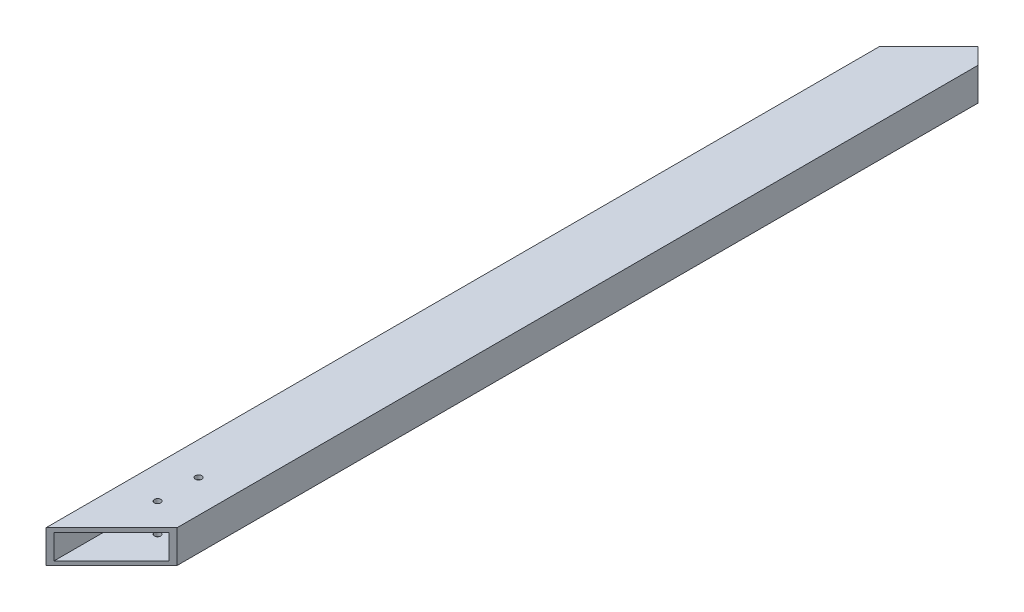
SolidWorks part; units mm, degrees
material "1060 Alloy"
ref_plane "Front Plane" through (0, 0, 0) normal (0, 0, 1) x (1, 0, 0)
ref_plane "Top Plane" through (0, 0, 0) normal (0, 1, 0) x (1, 0, 0)
ref_plane "Right Plane" through (0, 0, 0) normal (1, 0, 0) x (0, 0, -1)
sketch "Sketch1" plane through (0, 0, 0) normal (0, 0, 1) x (1, 0, 0)
  line L0 (22.225, 9.525) -> (-22.225, 9.525)
  line L1 (25.4, -12.7) -> (-25.4, -12.7)
  line L2 (25.4, -12.7) -> (25.4, 12.7)
  line L3 (25.4, 12.7) -> (-25.4, 12.7)
  line L4 (-25.4, -12.7) -> (-25.4, 12.7)
  line L5 (25.4, -12.7) -> (-25.4, 12.7) construction
  line L6 (25.4, 12.7) -> (-25.4, -12.7) construction
  line L7 (-22.225, -9.525) -> (-22.225, 9.525)
  line L8 (22.225, -9.525) -> (-22.225, -9.525)
  line L9 (22.225, -9.525) -> (22.225, 9.525)
  point P0 (0, 0)
  dimension "D1" = 25.4
  dimension "D2" = 50.8
  dimension "D3" = 3.175
extrude "Boss-Extrude1" add sketch "Sketch1" along normal blind 697.2046
sketch "Sketch2" plane through (0, 12.7, 0) normal (0, 1, 0) x (1, 0, 0)
  line L0 (-25.4, -697.2046) -> (25.4, -646.4046)
  line L1 (25.4, -697.2046) -> (25.4, 0) construction
  line L2 (25.4, -646.4046) -> (25.4, -697.2046)
  line L3 (25.4, -697.2046) -> (-25.4, -697.2046)
  line L4 (25.4, 0) -> (-25.4, -50.8)
  line L6 (-25.4, -697.2046) -> (-25.4, 0) construction
  line L7 (-25.4, -50.8) -> (-25.4, 0)
  line L8 (-25.4, 0) -> (25.4, 0)
  dimension "D1" = 45
  dimension "D2" = 45
extrude "Cut-Extrude1" cut sketch "Sketch2" against normal through all
sketch "Sketch3" plane through (0, 12.7, 0) normal (0, 1, 0) x (1, 0, 0)
  line L0 (25.4, 0) -> (25.4, -25.2984)
  line L1 (25.4, -646.4046) -> (25.4, 0) construction
  line L2 (25.4, -25.2984) -> (12.7508, -12.6492)
  line L4 (25.4, 0) -> (12.7508, -12.6492)
  dimension "D1" = 25.2984
  dimension "D2" = 45
extrude "Cut-Extrude3" cut sketch "Sketch3" against normal through all
hole_wizard "#10 (0.1935) Diameter Hole1" positions "Sketch4" profile "Sketch5" hole size "#10" standard "ANSI Inch" end condition through all
sketch "Sketch4" plane through (0, -12.7, 0) normal (0, -1, 0) x (-1, 0, 0)
  point P0 (0, -604.3205)
  point P3 (0, -636.0705)
sketch "Sketch5" plane through (0, -12.7, 604.3205) normal (1, 0, 0) x (0, 0, -1)
  line L0 (0, 0) -> (0, 25.4)
  line L1 (0, 25.4) -> (2.4574, 25.4)
  line L2 (2.4574, 25.4) -> (2.4574, 0)
  line L5 (2.4574, 0) -> (0, 0)
  line L11 (0, -6.35) -> (0, 107.95) construction
  dimension "Thru Hole Dia." = 4.9149
  dimension "Thru Hole Depth" = 25.4
